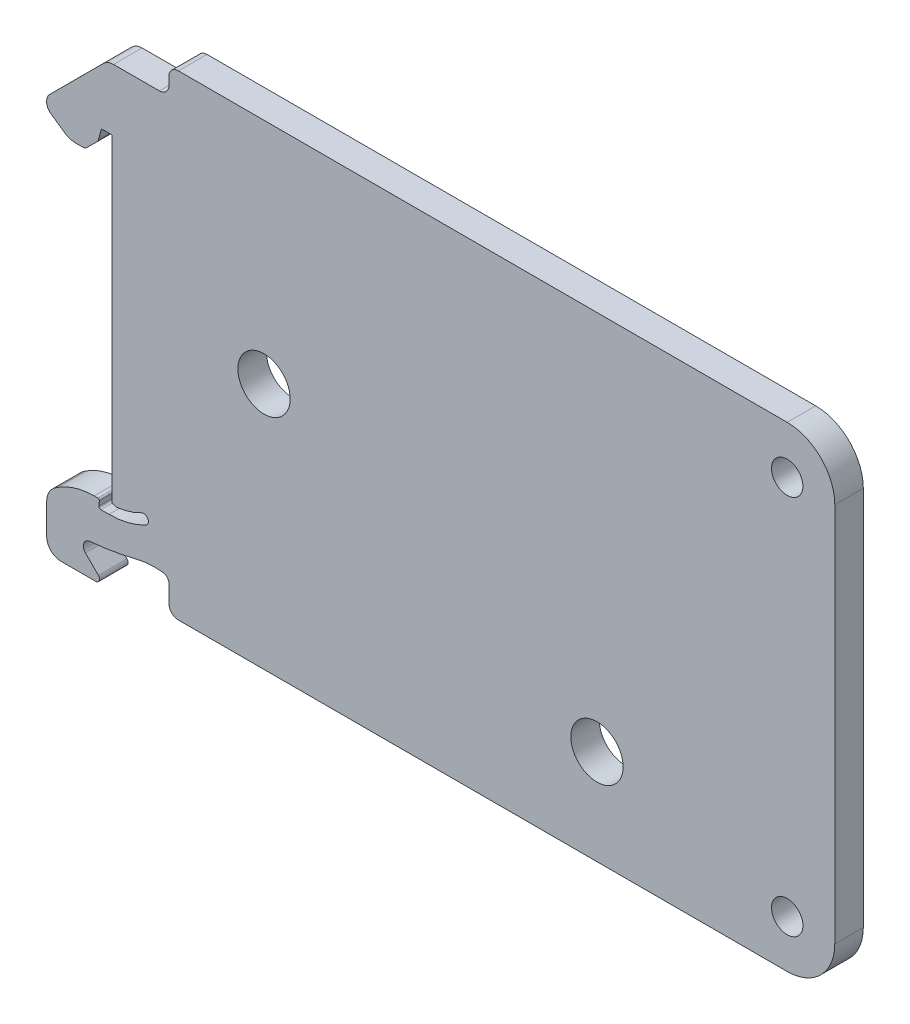
SolidWorks part; units mm, degrees
ref_plane "Front Plane" through (0, 0, 0) normal (0, 0, 1) x (1, 0, 0)
ref_plane "Top Plane" through (0, 0, 0) normal (0, 1, 0) x (1, 0, 0)
ref_plane "Right Plane" through (0, 0, 0) normal (1, 0, 0) x (0, 0, -1)
sketch "Sketch1" plane through (0, 0, 0) normal (0, 0, 1) x (1, 0, 0)
  line L0 (-27.5, 65.9546) -> (22.5, 65.9546) construction
  line L1 (-27.5, 40.9546) -> (-27.5, 43.7794)
  line L2 (-27.5, 90.9546) -> (-27.5, 88.1297)
  line L3 (17.5, 50.9546) -> (-17.5, 66.9546) construction
  line L4 (-27.5, 40.9546) -> (22.5, 40.9546)
  line L5 (22.5, 40.9546) -> (22.5, 90.9546)
  line L6 (22.5, 90.9546) -> (-27.5, 90.9546)
  line L7 (22.5, 90.5) -> (22.5, 0) construction
  circle A2 centre (-17.5, 66.9546) radius 2.75
  circle A3 centre (17.5, 50.9546) radius 2.75
  point P12 (-6.6368, 68.0728)
  line B0 (-27.5, 43.7794) -> (-27.5, 88.1297)
  line B1 (-27.5, 88.1297) -> (-33.323, 88.1297)
  line B2 (-34.3832, 87.6909) -> (-40.0568, 82.0229)
  line B3 (-40.35, 81.3155) -> (-40.35, 81.1808)
  line B4 (-39.9236, 80.3616) -> (-38.4666, 79.3414)
  line B5 (-37.3194, 78.9797) -> (-36.5071, 78.9797)
  line B6 (-36.1536, 79.1261) -> (-35.0425, 80.2372)
  line B7 (-34.913, 80.4614) -> (-34.6, 81.6297)
  line B8 (-34.6, 81.6297) -> (-33.5, 81.6297)
  line B9 (-33.5, 81.6297) -> (-33.5, 48.0769)
  line B10 (-33.5, 48.0769) -> (-33.3, 48.0769)
  line B11 (-33.8, 46.9297) -> (-34.6605, 46.9297)
  line B12 (-34.8597, 47.1471) -> (-34.8143, 47.6666)
  line B13 (-34.9637, 47.8297) -> (-35.3565, 47.8297)
  line B14 (-40.35, 44.8393) -> (-40.35, 41.6297)
  line B15 (-38.85, 40.1297) -> (-35.1929, 40.1297)
  line B16 (-34.9101, 40.8125) -> (-36.2797, 42.1821)
  arc B17 (-33.323, 88.1297) -> (-34.3832, 87.6909) centre (-33.323, 86.6297) ccw
  arc B18 (-40.0568, 82.0229) -> (-40.35, 81.3155) centre (-39.35, 81.3155) ccw
  arc B19 (-40.35, 81.1808) -> (-39.9236, 80.3616) centre (-39.35, 81.1808) ccw
  arc B20 (-38.4666, 79.3414) -> (-37.3194, 78.9797) centre (-37.3194, 80.9797) ccw
  arc B21 (-36.5071, 78.9797) -> (-36.1536, 79.1261) centre (-36.5071, 79.4797) ccw
  arc B22 (-35.0425, 80.2372) -> (-34.913, 80.4614) centre (-35.396, 80.5908) ccw
  arc B23 (-33.3, 48.0769) -> (-32.9412, 47.9804) centre (-33, 48.4769) ccw
  arc B24 (-32.9412, 47.9804) -> (-30.384, 48.7783) centre (-33.8, 55.2297) ccw
  arc B25 (-29.916, 47.8945) -> (-30.384, 48.7783) centre (-30.15, 48.3364) ccw
  arc B26 (-33.8, 46.9297) -> (-29.916, 47.8945) centre (-33.8, 55.2297) ccw
  arc B27 (-34.8597, 47.1471) -> (-34.6605, 46.9297) centre (-34.6605, 47.1297) ccw
  arc B28 (-34.8143, 47.6666) -> (-34.9637, 47.8297) centre (-34.9637, 47.6797) ccw
  arc B29 (-35.3565, 47.8297) -> (-39.1546, 46.7097) centre (-35.3565, 40.8297) ccw
  arc B30 (-39.1546, 46.7097) -> (-39.51, 46.4685) centre (-34, 38.7297) ccw
  arc B31 (-39.51, 46.4685) -> (-40.35, 44.8393) centre (-38.35, 44.8393) ccw
  arc B32 (-40.35, 41.6297) -> (-38.85, 40.1297) centre (-38.85, 41.6297) ccw
  arc B33 (-35.1929, 40.1297) -> (-34.9101, 40.8125) centre (-35.1929, 40.5297) ccw
  arc B34 (-35.8167, 43.4594) -> (-36.2797, 42.1821) centre (-35.7493, 42.7125) ccw
  arc B35 (-35.8167, 43.4594) -> (-30.8576, 44.3024) centre (-38.7, 75.4297) ccw
  arc B36 (-28.115, 44.4742) -> (-30.8576, 44.3024) centre (-29.0253, 37.0297) ccw
  arc B37 (-27.5, 43.7794) -> (-28.115, 44.4742) centre (-28.2, 43.7794) ccw
  dimension "D1" = 50
  dimension "D3" = 5.5
  dimension "D2" = 50
  dimension "D4" = 35
  dimension "D5" = 16
  dimension "D6" = 40
  dimension "D7" = 5
sketch_block_instance "Block1-1"
sketch_block "Block1"
extrude "Boss-Extrude1" add sketch "Sketch1" along normal blind 3
sketch "Sketch2" plane through (0, 0, 3) normal (0, 0, 1) x (1, 0, 0)
  line L0 (-27.5, 90.9546) -> (42.5, 90.9546)
  line L2 (-27.5, 40.9546) -> (-27.5, 90.9546)
  line L9 (42.5, 90.9546) -> (42.5, 40.9546)
  line L10 (42.5, 40.9546) -> (-27.5, 40.9546)
  line L11 (22.5, 40.9546) -> (22.5, 90.9546) construction
  circle A1 centre (-17.5, 66.9546) radius 2.75
  circle A2 centre (-17.5, 66.9546) radius 2.75 construction
  circle A4 centre (17.5, 50.9546) radius 2.75
  circle A5 centre (17.5, 50.9546) radius 2.75 construction
  dimension "D1" = 50
  dimension "D2" = 20
extrude "Boss-Extrude2" add sketch "Sketch2" against normal up to surface (3 mm away) up to face at (-32.0975, 60.4081, 0)
fillet "Fillet1" radius 5 2 edges at (42.5, 40.9546, 1.5) (42.5, 90.9546, 1.5)
hole_wizard "Tap Drill for M4x0.7 Tap1" positions "Sketch3" profile "Sketch4" hole size "M4x0.7" standard "ANSI Metric"
sketch "Sketch3" plane through (0, 0, 3) normal (0, 0, 1) x (1, 0, 0)
  arc A0 (42.5, 85.9546) -> (37.5, 90.9546) centre (37.5, 85.9546) ccw construction
  arc A1 (37.5, 40.9546) -> (42.5, 45.9546) centre (37.5, 45.9546) ccw construction
  point P0 (37.5, 45.9546)
  point P2 (37.5, 85.9546)
sketch "Sketch4" plane through (37.5, 45.9546, 3) normal (1, 0, 0) x (0, -1, 0)
  line L0 (0, 0) -> (0, 5.9914)
  line L1 (0, 5.9914) -> (1.65, 5)
  line L2 (1.65, 5) -> (1.65, 0)
  line L5 (1.65, 0) -> (0, 0)
  line L10 (0, 5.9914) -> (-1.65, 5) construction
  line L11 (0, -6.35) -> (0, 107.95) construction
  dimension "Hole Dia." = 3.3
  dimension "Hole Depth" = 5
  dimension "Drill Angle" = 118
fillet "Fillet2" radius 1 3 edges at (-27.5, 90.9546, 1.5) (-27.5, 88.1297, 1.5) (-27.5, 40.9546, 1.5)
